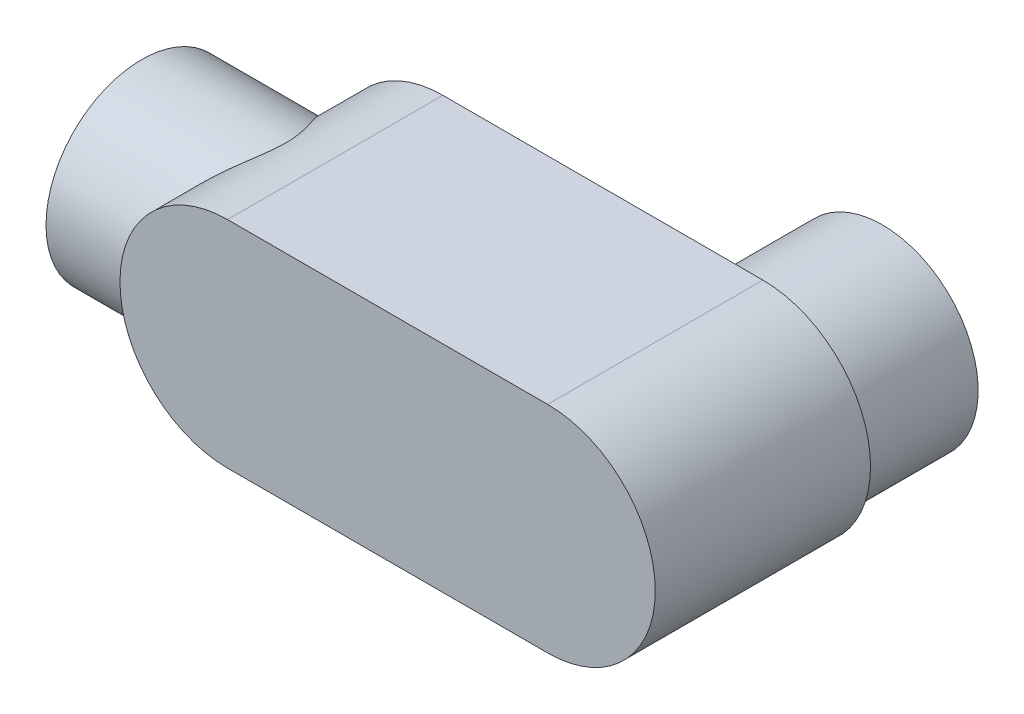
SolidWorks part; units mm, degrees
ref_plane "Alzado" through (0, 0, 0) normal (0, 0, 1) x (1, 0, 0)
ref_plane "Planta" through (0, 0, 0) normal (0, 1, 0) x (1, 0, 0)
ref_plane "Vista lateral" through (0, 0, 0) normal (1, 0, 0) x (0, 0, -1)
sketch "Croquis1" plane through (0, 0, 0) normal (0, 0, 1) x (1, 0, 0)
  line L0 (-43.5405, 0) -> (23.3595, 0) construction
  line L1 (-43.5405, 22.5) -> (23.3595, 22.5)
  line L2 (-43.5405, -22.5) -> (23.3595, -22.5)
  arc A0 (-43.5405, 22.5) -> (-43.5405, -22.5) centre (-43.5405, 0) ccw
  arc A1 (23.3595, -22.5) -> (23.3595, 22.5) centre (23.3595, 0) ccw
  point P3 (-10.0905, 0)
  point P8 (-66.0405, 0)
  point P9 (45.8595, 0)
  point P10 (0, -0.2584)
  point P11 (0, -0.2584)
  point P12 (0, -0.2584)
  point P13 (0, -0.2584)
  dimension "D1" = 111.9
  dimension "D2" = 43.5405
  dimension "D3" = 45
extrude "Saliente-Extruir1" add sketch "Croquis1" along normal blind 45
sketch "Croquis2" plane through (0, 0, 0) normal (0, 0, -1) x (-1, 0, 0)
  circle A0 centre (-23.3595, 0) radius 20
  dimension "D1" = 40
extrude "Saliente-Extruir2" add sketch "Croquis2" along normal blind 25 and the other way blind 45
sketch "Croquis3" plane through (0, 0, -25) normal (0, 0, -1) x (-1, 0, 0)
  circle A0 centre (-23.3595, 0) radius 20
  dimension "D1" = 40
sketch "Croquis4" plane through (0, 0, -25) normal (0, 0, -1) x (-1, 0, 0)
  circle A0 centre (-23.3595, 0) radius 19.05
  dimension "D1" = 38.1
extrude "Cortar-Extruir3" cut sketch "Croquis4" against normal blind 69
sketch "Croquis5" plane through (0, 0, 0) normal (1, 0, 0) x (0, 0, -1)
  line L1 (0, -22.5) -> (0, 22.5) construction
  circle A0 centre (-22.5, 0) radius 20
  dimension "D1" = 40
  dimension "D2" = 22.5
extrude "Saliente-Extruir3" add sketch "Croquis5" against normal blind 84 and the other way blind 29.4954
sketch "Croquis8" plane through (-84, 0, 0) normal (-1, 0, 0) x (0, 0, 1)
  circle A0 centre (22.4205, 0) radius 19.05
  dimension "D1" = 38.1
extrude "Cortar-Extruir6" cut sketch "Croquis8" against normal blind 114
